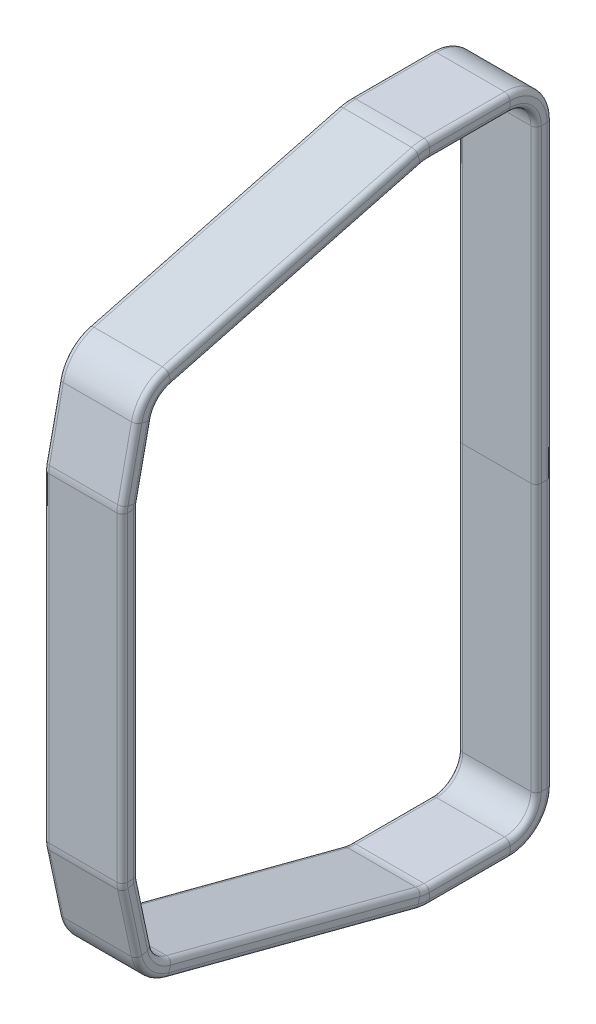
SolidWorks part; units mm, degrees
material "Nylon"
ref_plane "Front Plane" through (0, 0, 0) normal (0, 0, 1) x (1, 0, 0)
ref_plane "Top Plane" through (0, 0, 0) normal (0, 1, 0) x (1, 0, 0)
ref_plane "Right Plane" through (0, 0, 0) normal (1, 0, 0) x (0, 0, -1)
ref_plane "Plane1" through (-39.0995, 0, 0) normal (1, 0, 0) x (0, 0, -1)
sketch "Sketch2" plane through (-39.0995, 0, 0) normal (1, 0, 0) x (0, 0, -1)
  line L0 (0.8255, -25.8837) -> (0.8255, 29.9963) construction
  line L1 (0.8255, -25.8837) -> (0.8255, 29.9963)
  line L2 (-9.525, 32.5363) -> (1.196, 32.5363) construction
  line L3 (-9.525, 32.5363) -> (-1.7145, 32.5363)
  line L4 (-34.4892, 26.1034) -> (-10.3296, 32.4327)
  line L5 (0.8255, 2.0563) -> (-40.6949, 2.0563) construction
  line L6 (-37.6654, 17.8861) -> (-36.3301, 24.174)
  line L7 (-37.7, 17.5563) -> (-37.5, 17.5563) construction
  line L8 (-37.7, 17.5563) -> (-35.6382, 17.5563) construction
  line L9 (-37.7, 17.5563) -> (-37.7, -13.4437) construction
  line L10 (-37.7, 17.5563) -> (-37.7, -13.4437)
  line L11 (-9.525, -28.4237) -> (-1.7145, -28.4237)
  line L13 (-34.4892, -21.9907) -> (-10.3296, -28.32)
  line L14 (-37.6654, -13.7734) -> (-36.3301, -20.0613)
  arc A0 (0.8255, 29.9963) -> (-1.7145, 32.5363) centre (-1.7145, 29.9963) ccw construction
  arc A1 (0.8255, 29.9963) -> (-1.7145, 32.5363) centre (-1.7145, 29.9963) ccw
  arc A2 (-9.525, 32.5363) -> (-12.7, 29.3613) centre (-9.525, 29.3613) ccw construction
  arc A3 (-9.525, 32.5363) -> (-10.3296, 32.4327) centre (-9.525, 29.3613) ccw
  arc A4 (-33.8455, 26.1863) -> (-36.3855, 23.6463) centre (-33.8455, 23.6463) ccw construction
  arc A5 (-34.4892, 26.1034) -> (-36.3301, 24.174) centre (-33.8455, 23.6463) ccw
  arc A6 (-37.7, 17.5563) -> (-37.6654, 17.8861) centre (-36.1125, 17.5563) cw
  arc A7 (0.8255, -25.8837) -> (-1.7145, -28.4237) centre (-1.7145, -25.8837) cw
  arc A8 (-9.525, -28.4237) -> (-10.3296, -28.32) centre (-9.525, -25.2487) cw
  arc A9 (-34.4892, -21.9907) -> (-36.3301, -20.0613) centre (-33.8455, -19.5337) cw
  arc A10 (-37.7, -13.4437) -> (-37.6654, -13.7734) centre (-36.1125, -13.4437) ccw
  point P32 (-37.7, 2.0563)
  dimension "D1" = 1.5875
sketch "Sketch3" plane through (0, 0, 0) normal (0, 1, 0) x (1, 0, 0)
  line L1 (-35.2895, 0.8255) -> (-42.9095, 0.8255)
  line L2 (-35.2895, 0.8255) -> (-35.2895, 2.413)
  line L3 (-35.2895, 2.413) -> (-42.9095, 2.413)
  line L4 (-42.9095, 0.8255) -> (-42.9095, 2.413)
  point P4 (-39.0995, 0.8255)
  dimension "D1" = 1.5875
  dimension "D2" = 7.62
sweep "Sweep1" add profiles "Sketch3" path "Sketch2"
fillet "Fillet1" radius 0.508 68 edges at (-35.2895, -12.9418, -2.413) (-42.9095, -12.9418, -2.413) (-42.9095, -12.9418, -0.8255) (-35.2895, -12.9418, -0.8255) (-35.2895, -28.8022, -1.2041) (-42.9095, -28.8022, -1.2041) (-42.9095, -27.6797, -0.0816) (-35.2895, -27.6797, -0.0816) (-35.2895, 30.8037, 22.8117) (-42.9095, 30.8037, 22.8117) (-42.9095, 29.2681, 22.4094) (-35.2895, 29.2681, 22.4094) (-35.2895, 34.0848, 10.1335) (-42.9095, 34.0848, 10.1335) (-42.9095, 32.5103, 9.9306) (-35.2895, 32.5103, 9.9306) (-35.2895, 34.1238, 5.6197) (-42.9095, 34.1238, 5.6197) (-42.9095, 32.5363, 5.6197) (-35.2895, 32.5363, 5.6197) (-35.2895, 32.9149, -1.2041) (-42.9095, 32.9149, -1.2041) (-42.9095, 31.7924, -0.0816) (-35.2895, 31.7924, -0.0816) (-35.2895, 14.9982, -2.413) (-42.9095, 14.9982, -2.413) (-35.2895, 14.9982, -0.8255) (-42.9095, 14.9982, -0.8255) (-35.2895, -30.0112, 5.6197) (-42.9095, -30.0112, 5.6197) (-42.9095, -28.4237, 5.6197) (-35.2895, -28.4237, 5.6197) (-35.2895, -29.9721, 10.1335) (-42.9095, -29.9721, 10.1335) (-42.9095, -28.3976, 9.9306) (-35.2895, -28.3976, 9.9306) (-35.2895, -26.6911, 22.8117) (-42.9095, -26.6911, 22.8117) (-42.9095, -25.1554, 22.4094) (-35.2895, -25.1554, 22.4094) (-35.2895, -22.3829, 36.8318) (-42.9095, -22.3829, 36.8318) (-42.9095, -21.287, 35.6832) (-35.2895, -21.287, 35.6832) (-35.2895, -17.2471, 38.5506) (-42.9095, -17.2471, 38.5506) (-42.9095, -16.9174, 36.9977) (-35.2895, -16.9174, 36.9977) (-35.2895, -13.7752, 39.2701) (-42.9095, -13.7752, 39.2701) (-42.9095, -13.6094, 37.6913) (-35.2895, -13.6094, 37.6913) (-35.2895, 2.0563, 39.2875) (-42.9095, 2.0563, 39.2875) (-42.9095, 2.0563, 37.7) (-35.2895, 2.0563, 37.7) (-35.2895, 17.8879, 39.2701) (-42.9095, 17.8879, 39.2701) (-42.9095, 17.7221, 37.6913) (-35.2895, 17.7221, 37.6913) (-35.2895, 21.3598, 38.5506) (-42.9095, 21.3598, 38.5506) (-42.9095, 21.03, 36.9977) (-35.2895, 21.03, 36.9977) (-35.2895, 26.4956, 36.8318) (-42.9095, 26.4956, 36.8318) (-42.9095, 25.3997, 35.6832) (-35.2895, 25.3997, 35.6832)
